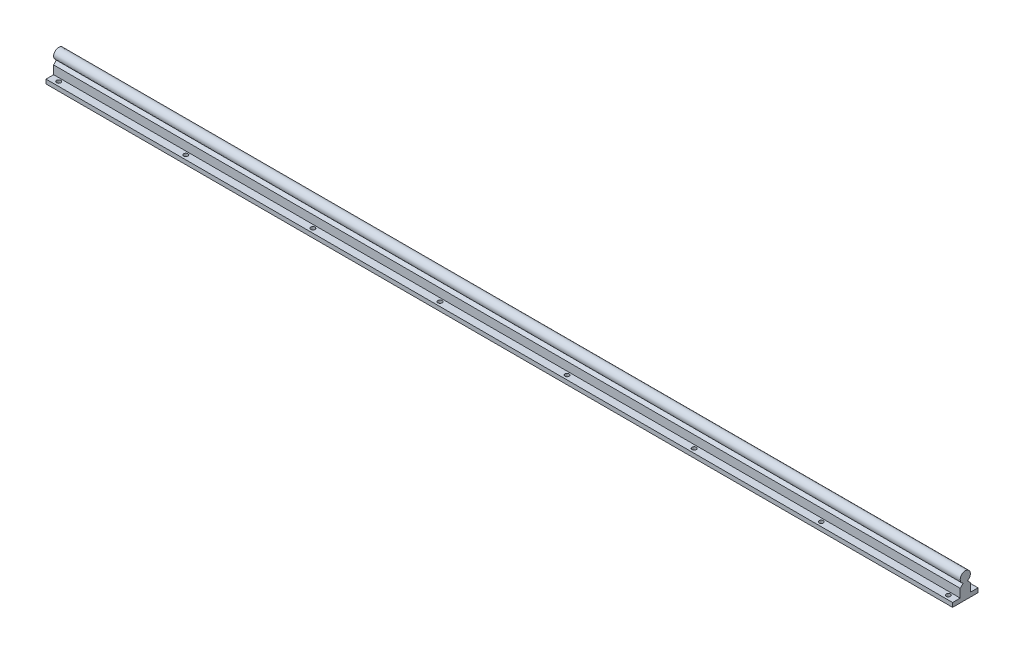
SolidWorks part; units mm, degrees
ref_plane "Спереди" through (0, 0, 0) normal (0, 0, 1) x (1, 0, 0)
ref_plane "Сверху" through (0, 0, 0) normal (0, 1, 0) x (1, 0, 0)
ref_plane "Справа" through (0, 0, 0) normal (1, 0, 0) x (0, 0, -1)
sketch "Эскиз1" plane through (0, 0, 0) normal (1, 0, 0) x (0, 0, -1)
  line L0 (-6, 15) -> (-2.5, 18.5456)
  line L1 (-15, 5) -> (-6, 5)
  line L2 (-15, 5) -> (-15, 0)
  line L3 (-15, 0) -> (15, 0)
  line L4 (15, 5) -> (15, 0)
  line L6 (-15, 2.5) -> (15, 2.5) construction
  line L8 (-6, 15) -> (-6, 5)
  line L10 (6, 15) -> (6, 5)
  line L11 (0, 0) -> (0, 18) construction
  line L13 (6, 15) -> (2.5, 18.5456)
  line L14 (6, 5) -> (15, 5)
  arc A0 (2.5, 18.5456) -> (-2.5, 18.5456) centre (0, 24) ccw
  point P4 (0, -2.0656)
  point P5 (0, 0)
  point P7 (0, 0)
  point P13 (0, 0)
  point P15 (0, 0)
  point P16 (6, 17.1489)
  point P17 (-2.8241, 18.7062)
  point P18 (6, 15.6712)
  point P19 (6, 11.7085)
  point P20 (0, 0)
  point P21 (0, 0)
  point P22 (0, 0)
  point P23 (0, 0)
  dimension "D5" = 12
  dimension "D6" = 30
  dimension "D1" = 5
  dimension "D2" = 30
  dimension "D3" = 12
  dimension "D4" = 5
  dimension "D7" = 10
extrude "Бобышка-Вытянуть1" add sketch "Эскиз1" against normal mid plane 1070
sketch "Эскиз2" plane through (0, 0, 0) normal (0, -1, 0) x (1, 0, 0)
  line L0 (0, 0) -> (-70.8439, 0) construction
  line L1 (-535, 15) -> (-535, -15) construction
  circle A0 centre (-525, 10) radius 2.5
  circle A1 centre (-525, -10) radius 2.5
  point P7 (0, 0)
  dimension "D1" = 5
  dimension "D2" = 20
  dimension "D3" = 10
extrude "Вырез-Вытянуть1" cut sketch "Эскиз2" against normal blind 1070
pattern_linear "Линейный массив1" count 8 spacing 150 along (1, 0, 0) of "Вырез-Вытянуть1"
